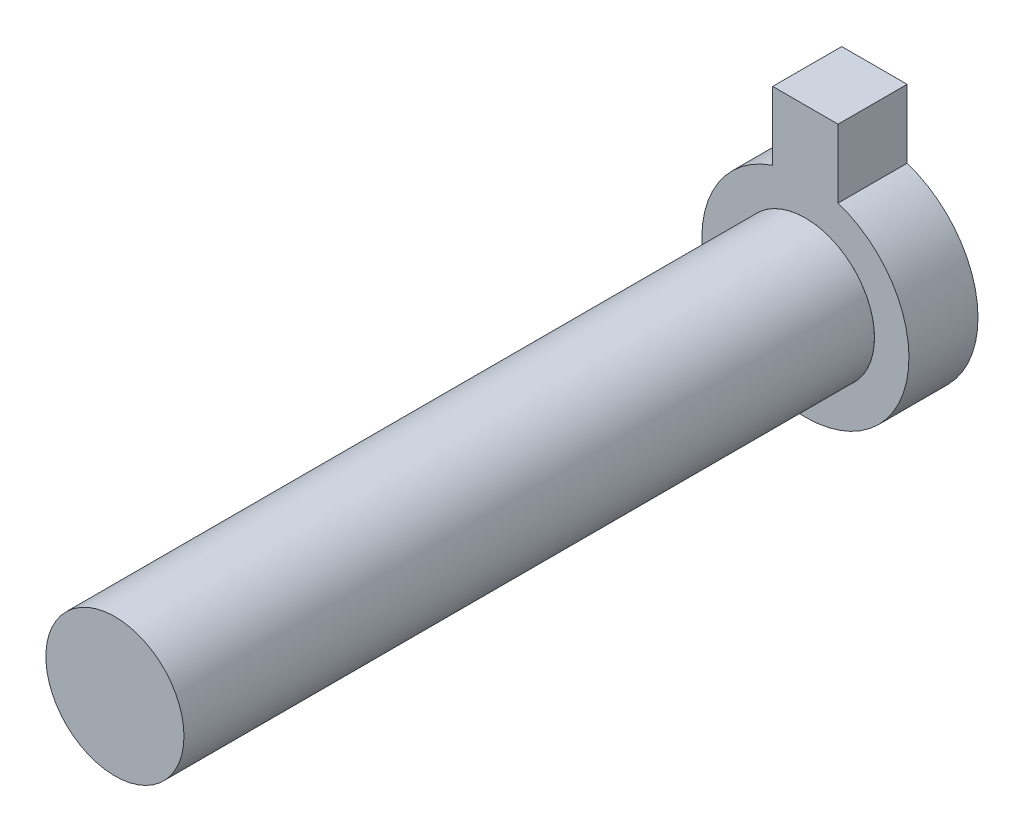
SolidWorks part; units mm, degrees
ref_plane "Front Plane" through (0, 0, 0) normal (0, 0, 1) x (1, 0, 0)
ref_plane "Top Plane" through (0, 0, 0) normal (0, 1, 0) x (1, 0, 0)
ref_plane "Right Plane" through (0, 0, 0) normal (1, 0, 0) x (0, 0, -1)
sketch "Sketch2" plane through (0, 0, 0) normal (1, 0, 0) x (0, 0, -1)
  line L0 (0, 0) -> (550, 0)
  line L1 (550, 0) -> (550, -75)
  line L2 (550, -75) -> (500, -75)
  line L3 (500, -75) -> (500, -50)
  line L4 (500, -50) -> (0, -50)
  line L5 (0, -50) -> (0, 0)
  dimension "D1" = 550
  dimension "D2" = 50
  dimension "D3" = 50
  dimension "D4" = 25
revolve "Revolve1" add sketch "Sketch2" angle 360 about L0
sketch "Sketch4" plane through (0, 0, -550) normal (0, 0, -1) x (-1, 0, 0)
  circle A0 centre (0, 0) radius 50
  dimension "D1" = 100
extrude "Cut-Extrude2" cut sketch "Sketch4" against normal blind 50
sketch "Sketch5" plane through (0, 0, -550) normal (0, 0, -1) x (-1, 0, 0)
  line L2 (-23.6859, 120.6612) -> (23.6859, 120.6612)
  line L3 (-23.6859, 120.6612) -> (-23.6859, 71.1616)
  line L5 (23.6859, 120.6612) -> (23.6859, 71.1616)
  line L6 (-23.6859, 120.6612) -> (23.6859, 71.1616) construction
  line L7 (-23.6859, 71.1616) -> (23.6859, 120.6612) construction
  circle A0 centre (0, 0) radius 75 construction
  arc A1 (-23.6859, 71.1616) -> (23.6859, 71.1616) centre (0, 0) cw
extrude "Boss-Extrude2" add sketch "Sketch5" against normal blind 50
